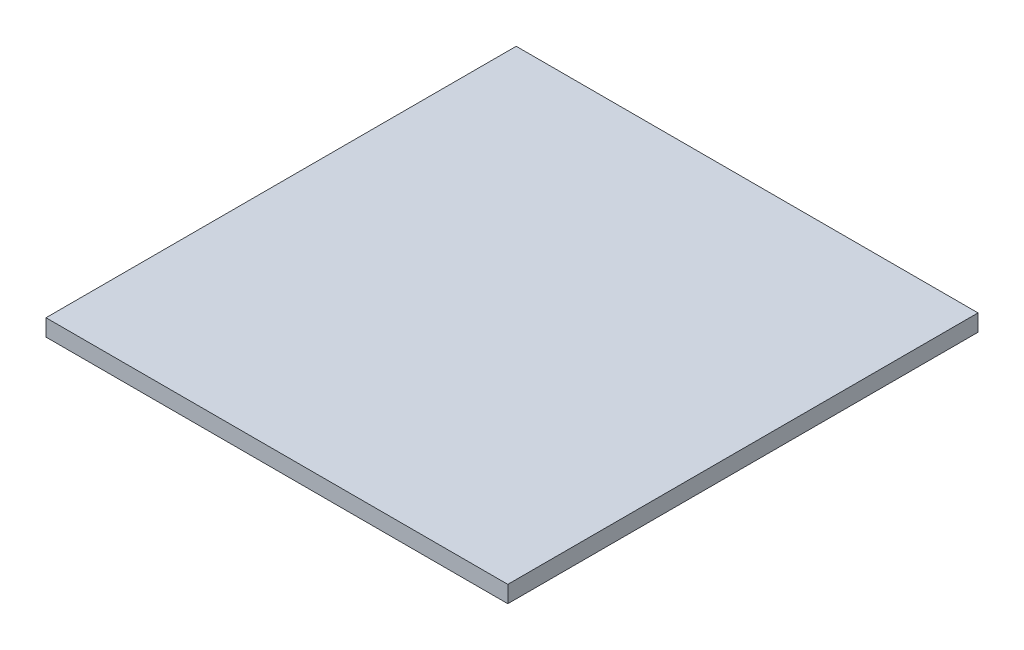
SolidWorks part; units mm, degrees
ref_plane "Ön Düzlem" through (0, 0, 0) normal (0, 0, 1) x (1, 0, 0)
ref_plane "Üst Düzlem" through (0, 0, 0) normal (0, 1, 0) x (1, 0, 0)
ref_plane "Sağ Düzlem" through (0, 0, 0) normal (1, 0, 0) x (0, 0, -1)
sketch "Çizim1" plane through (0, 0, 0) normal (1, 0, 0) x (0, 0, -1)
  line L0 (0, 0) -> (280, 0)
  line L1 (0, 10) -> (280, 10)
  line L2 (280, 10) -> (280, 0)
  line L3 (0, 10) -> (0, 0)
  dimension "D1" = 280
  dimension "D2" = 10
extrude "Yükseklik-Ekstrüzyon1" add sketch "Çizim1" along normal blind 275
